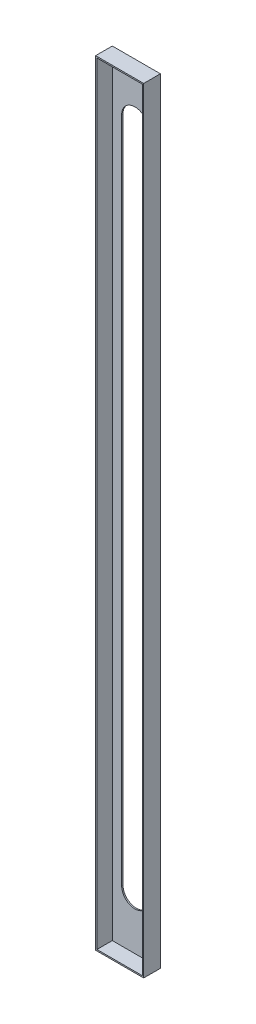
SolidWorks part; units mm, degrees
ref_plane "정면" through (0, 0, 0) normal (0, 0, 1) x (1, 0, 0)
ref_plane "윗면" through (0, 0, 0) normal (0, 1, 0) x (1, 0, 0)
ref_plane "우측면" through (0, 0, 0) normal (1, 0, 0) x (0, 0, -1)
sketch "스케치1" plane through (0, 0, 0) normal (0, 0, 1) x (1, 0, 0)
  line L1 (0, 0) -> (7.2, 0)
  line L2 (0, 0) -> (0, 116)
  line L3 (0, 116) -> (7.2, 116)
  line L4 (7.2, 0) -> (7.2, 116)
  dimension "D1" = 116
  dimension "D2" = 7.2
extrude "보스-돌출1" add sketch "스케치1" along normal blind 2.5
shell "쉘1" thickness 0.2
sketch "스케치2" plane through (0, 0, 0.2) normal (0, 0, 1) x (1, 0, 0)
  line L0 (0, 116) -> (0, 0) construction
  line L2 (5.6, 108) -> (5.6, 8)
  line L3 (1.6, 108) -> (1.6, 8)
  line L4 (7.2, 116) -> (0, 116) construction
  line L5 (0, 0) -> (7.2, 0) construction
  arc A0 (5.6, 108) -> (1.6, 108) centre (3.6, 108) ccw
  arc A1 (5.6, 8) -> (1.6, 8) centre (3.6, 8) cw
  point P15 (3.6, 110)
  point P18 (3.6, 6)
  point P21 (3.6, 0)
  dimension "D1" = 2
  dimension "D3" = 2
  dimension "D2" = 3.6
  dimension "D4" = 6
  dimension "D5" = 6
extrude "컷-돌출1" cut sketch "스케치2" against normal blind 2.5
